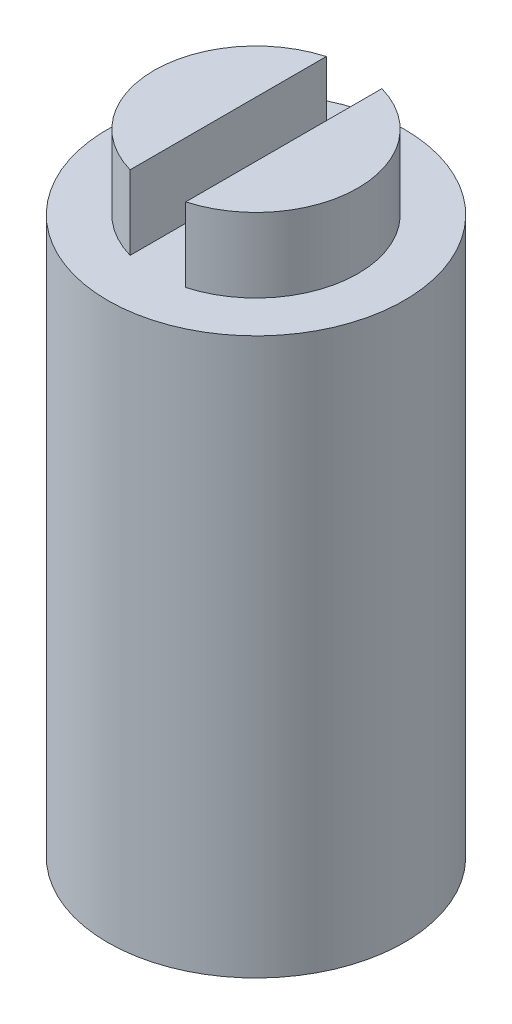
SolidWorks part; units mm, degrees
material "AISI 1015 Steel, Cold Drawn (SS)"
ref_plane "Front Plane" through (0, 0, 0) normal (0, 0, 1) x (1, 0, 0)
ref_plane "Top Plane" through (0, 0, 0) normal (0, 1, 0) x (1, 0, 0)
ref_plane "Right Plane" through (0, 0, 0) normal (1, 0, 0) x (0, 0, -1)
sketch "Sketch2" plane through (0, 0, 0) normal (0, 1, 0) x (1, 0, 0)
  circle A0 centre (0, 0) radius 4
  dimension "D1" = 8
extrude "Boss-Extrude1" add sketch "Sketch2" against normal blind 15
cosmetic thread "Cosmetic Thread1" parameters "D2"=6.619
sketch "Sketch3" plane through (0, 0, 0) normal (0, 1, 0) x (1, 0, 0)
  line L2 (-0.75, 2.6458) -> (-0.75, -2.6458)
  line L4 (0.75, 2.6458) -> (0.75, -2.6458)
  arc A0 (-0.75, 2.6458) -> (-0.75, -2.6458) centre (0, 0) ccw
  arc A1 (0.75, -2.6458) -> (0.75, 2.6458) centre (0, 0) ccw
  dimension "D1" = 5.5
  dimension "D2" = 1.5
extrude "Boss-Extrude2" add sketch "Sketch3" along normal blind 2
